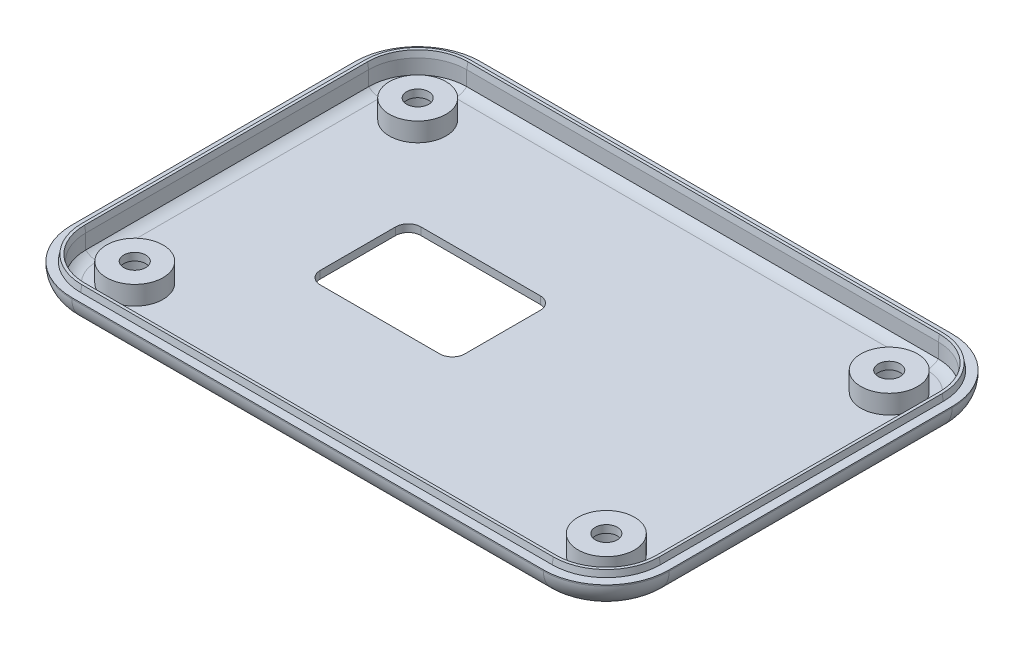
SolidWorks part; units mm, degrees
ref_plane "Front Plane" through (0, 0, 0) normal (0, 0, 1) x (1, 0, 0)
ref_plane "Top Plane" through (0, 0, 0) normal (0, 1, 0) x (1, 0, 0)
ref_plane "Right Plane" through (0, 0, 0) normal (1, 0, 0) x (0, 0, -1)
sketch "Sketch1" plane through (0, 0, 0) normal (0, 1, 0) x (1, 0, 0)
  line L1 (0, 0) -> (95, 0)
  line L2 (0, 0) -> (0, 65)
  line L3 (0, 65) -> (95, 65)
  line L4 (95, 0) -> (95, 65)
  dimension "D1" = 95
  dimension "D2" = 65
extrude "Boss-Extrude1" add sketch "Sketch1" along normal blind 4.2
fillet "Fillet1" radius 10 4 edges at (95, 2.1, 0) (95, 2.1, -65) (0, 2.1, -65) (0, 2.1, 0)
fillet "Fillet2" radius 4 8 edges at (92.0711, 0, -62.0711) (47.5, 0, -65) (2.9289, 0, -62.0711) (0, 0, -32.5) (2.9289, 0, -2.9289) (47.5, 0, 0) (92.0711, 0, -2.9289) (95, 0, -32.5)
shell "Shell1" thickness 1.2
sketch "Sketch5" plane through (0, 1.2, 0) normal (0, 1, 0) x (1, 0, 0)
  circle A0 centre (10, 55) radius 4.5
  circle A1 centre (85, 55) radius 4.5
  circle A2 centre (85, 10) radius 4.5
  circle A3 centre (10, 10) radius 4.5
  arc A4 (91, 55) -> (85, 61) centre (85, 55) ccw construction
  arc A5 (85, 4) -> (91, 10) centre (85, 10) ccw construction
  arc A6 (4, 10) -> (10, 4) centre (10, 10) ccw construction
  arc A7 (10, 61) -> (4, 55) centre (10, 55) ccw construction
  dimension "D1" = 9
extrude "Boss-Extrude3" add sketch "Sketch5" along normal up to surface (3 mm away) up to face at (47.5, 4.2, -32.5)
sketch "Sketch7" plane through (0, 4.2, 0) normal (0, 1, 0) x (1, 0, 0)
  circle A0 centre (10, 55) radius 1.75
  circle A1 centre (85, 55) radius 1.75
  circle A2 centre (85, 10) radius 1.75
  circle A3 centre (10, 10) radius 1.75
  dimension "D1" = 3.5
extrude "Cut-Extrude2" cut sketch "Sketch7" against normal blind 10
sketch "Sketch8" plane through (0, 4.2, 0) normal (0, 1, 0) x (1, 0, 0)
  line L20 (1.2, 55) -> (1.2, 10) construction
  line L21 (10, 1.2) -> (85, 1.2) construction
  line L22 (93.8, 10) -> (93.8, 55) construction
  line L23 (85, 63.8) -> (10, 63.8) construction
  line L24 (85, 62.8) -> (10, 62.8)
  line L25 (2.2, 55) -> (2.2, 10)
  line L26 (10, 2.2) -> (85, 2.2)
  line L27 (92.8, 10) -> (92.8, 55)
  line L28 (85, 62.8) -> (10, 62.8)
  line L29 (2.2, 55) -> (2.2, 10)
  line L30 (10, 2.2) -> (85, 2.2)
  line L31 (92.8, 10) -> (92.8, 55)
  line L32 (1.2, 55) -> (1.2, 10)
  line L33 (10, 1.2) -> (85, 1.2)
  line L34 (93.8, 10) -> (93.8, 55)
  line L35 (85, 63.8) -> (10, 63.8)
  arc A16 (10, 63.8) -> (1.2, 55) centre (10, 55) ccw construction
  arc A17 (1.2, 10) -> (10, 1.2) centre (10, 10) ccw construction
  arc A18 (85, 1.2) -> (93.8, 10) centre (85, 10) ccw construction
  arc A19 (93.8, 55) -> (85, 63.8) centre (85, 55) ccw construction
  arc A20 (92.8, 55) -> (85, 62.8) centre (85, 55) ccw
  arc A21 (10, 62.8) -> (2.2, 55) centre (10, 55) ccw
  arc A22 (2.2, 10) -> (10, 2.2) centre (10, 10) ccw
  arc A23 (85, 2.2) -> (92.8, 10) centre (85, 10) ccw
  arc A24 (92.8, 55) -> (85, 62.8) centre (85, 55) ccw
  arc A25 (10, 62.8) -> (2.2, 55) centre (10, 55) ccw
  arc A26 (2.2, 10) -> (10, 2.2) centre (10, 10) ccw
  arc A27 (85, 2.2) -> (92.8, 10) centre (85, 10) ccw
  arc A28 (10, 63.8) -> (1.2, 55) centre (10, 55) ccw
  arc A29 (1.2, 10) -> (10, 1.2) centre (10, 10) ccw
  arc A30 (85, 1.2) -> (93.8, 10) centre (85, 10) ccw
  arc A31 (93.8, 55) -> (85, 63.8) centre (85, 55) ccw
  dimension "D1" = 1
extrude "Boss-Extrude4" add sketch "Sketch8" against normal up to next
sketch "Sketch11" plane through (0, 4.2, 0) normal (0, 1, 0) x (1, 0, 0)
  line L25 (92.8, 10) -> (92.8, 55) construction
  line L26 (85, 62.8) -> (10, 62.8) construction
  line L27 (2.2, 55) -> (2.2, 10) construction
  line L28 (10, 2.2) -> (85, 2.2) construction
  line L29 (93.6, 10) -> (93.6, 55)
  line L30 (85, 63.6) -> (10, 63.6)
  line L31 (1.4, 55) -> (1.4, 10)
  line L32 (10, 1.4) -> (85, 1.4)
  line L33 (93.6, 10) -> (93.6, 55)
  line L34 (85, 63.6) -> (10, 63.6)
  line L35 (1.4, 55) -> (1.4, 10)
  line L36 (10, 1.4) -> (85, 1.4)
  line L37 (92.8, 10) -> (92.8, 55)
  line L38 (85, 62.8) -> (10, 62.8)
  line L39 (2.2, 55) -> (2.2, 10)
  line L40 (10, 2.2) -> (85, 2.2)
  arc A20 (85, 2.2) -> (92.8, 10) centre (85, 10) ccw construction
  arc A21 (92.8, 55) -> (85, 62.8) centre (85, 55) ccw construction
  arc A22 (10, 62.8) -> (2.2, 55) centre (10, 55) ccw construction
  arc A23 (2.2, 10) -> (10, 2.2) centre (10, 10) ccw construction
  arc A24 (85, 1.4) -> (93.6, 10) centre (85, 10) ccw
  arc A25 (93.6, 55) -> (85, 63.6) centre (85, 55) ccw
  arc A26 (10, 63.6) -> (1.4, 55) centre (10, 55) ccw
  arc A27 (1.4, 10) -> (10, 1.4) centre (10, 10) ccw
  arc A28 (85, 1.4) -> (93.6, 10) centre (85, 10) ccw
  arc A29 (93.6, 55) -> (85, 63.6) centre (85, 55) ccw
  arc A30 (10, 63.6) -> (1.4, 55) centre (10, 55) ccw
  arc A31 (1.4, 10) -> (10, 1.4) centre (10, 10) ccw
  arc A32 (85, 2.2) -> (92.8, 10) centre (85, 10) ccw
  arc A33 (92.8, 55) -> (85, 62.8) centre (85, 55) ccw
  arc A34 (10, 62.8) -> (2.2, 55) centre (10, 55) ccw
  arc A35 (2.2, 10) -> (10, 2.2) centre (10, 10) ccw
  dimension "D1" = 0.8
extrude "Boss-Extrude5" add sketch "Sketch11" along normal blind 1 draft 10
sketch "Sketch12" plane through (0, 0, 0) normal (0, -1, 0) x (1, 0, 0)
  circle A0 centre (10, -10) radius 3.5
  circle A1 centre (85, -10) radius 3.5
  circle A2 centre (85, -55) radius 3.5
  circle A3 centre (10, -55) radius 3.5
  dimension "D1" = 7
extrude "Cut-Extrude3" cut sketch "Sketch12" against normal blind 3
sketch "Sketch13" plane through (0, 0, 0) normal (0, -1, 0) x (1, 0, 0)
  line L0 (91, -55) -> (91, -10) construction
  line L1 (46, -40.5) -> (23, -40.5)
  line L2 (46, -40.5) -> (46, -24.5)
  line L3 (46, -24.5) -> (23, -24.5)
  line L4 (23, -40.5) -> (23, -24.5)
  point P6 (91, -32.5)
  point P7 (46, -32.5)
  dimension "D1" = 23
  dimension "D2" = 16
  dimension "D3" = 45
extrude "Cut-Extrude4" cut sketch "Sketch13" against normal through all
fillet "Fillet3" radius 2 4 edges at (46, 0.6, -24.5) (23, 0.6, -24.5) (23, 0.6, -40.5) (46, 0.6, -40.5)
equation "\"D3@Sketch4\"=21 * 2.54"
equation "\"D2@Sketch4\"=11*2.54"
